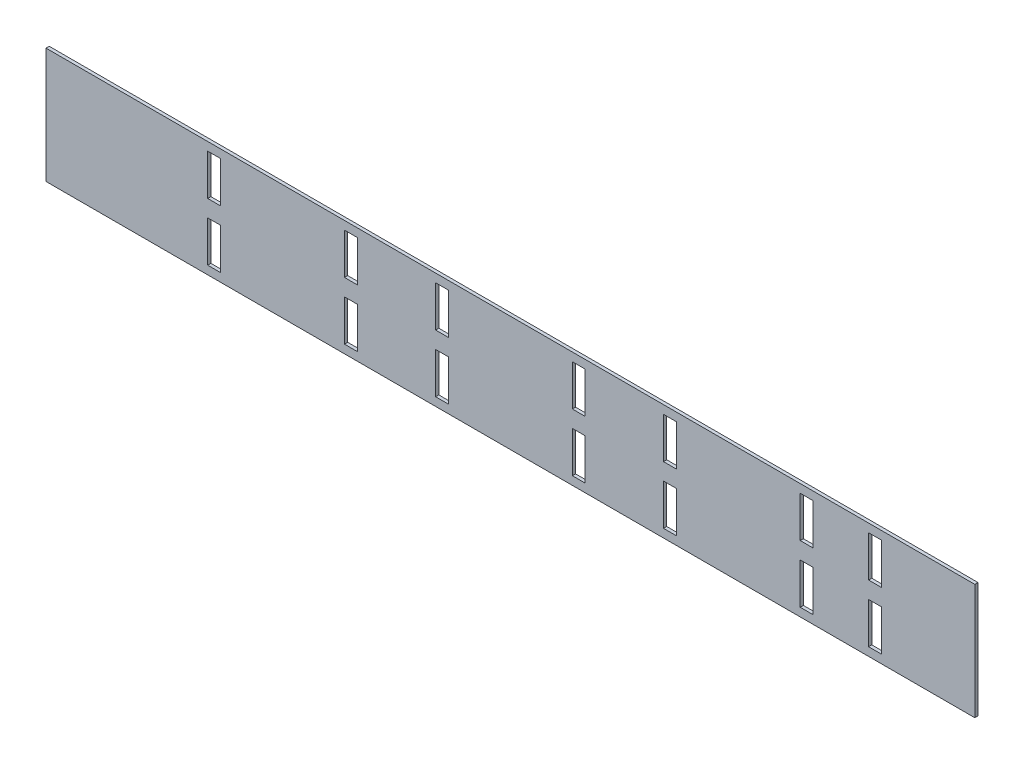
SolidWorks part; units mm, degrees
material "Acrylic (Medium-high impact)"
ref_plane "Front Plane" through (0, 0, 0) normal (0, 0, 1) x (1, 0, 0)
ref_plane "Top Plane" through (0, 0, 0) normal (0, 1, 0) x (1, 0, 0)
ref_plane "Right Plane" through (0, 0, 0) normal (1, 0, 0) x (0, 0, -1)
sketch "Sketch12" plane through (0, 0, 0) normal (0, 0, 1) x (1, 0, 0)
  line L0 (-148.2488, 58.6659) -> (312.4252, 58.6659)
  line L1 (-148.2488, 58.6659) -> (-148.2488, 1.3659)
  line L2 (-148.2488, 1.3659) -> (312.4252, 1.3659)
  line L3 (312.4252, 58.6659) -> (312.4252, 1.3659)
  line L4 (158.0086, 54.5003) -> (164.4098, 54.5003)
  line L5 (158.0086, 54.5003) -> (158.0086, 34.1803)
  line L6 (158.0086, 34.1803) -> (164.4098, 34.1803)
  line L7 (164.4098, 54.5003) -> (164.4098, 34.1803)
  line L8 (112.7966, 54.5003) -> (119.1978, 54.5003)
  line L9 (112.7966, 54.5003) -> (112.7966, 34.1803)
  line L10 (112.7966, 34.1803) -> (119.1978, 34.1803)
  line L11 (119.1978, 54.5003) -> (119.1978, 34.1803)
  line L12 (112.7966, 25.8491) -> (119.1978, 25.8491)
  line L13 (112.7966, 25.8491) -> (112.7966, 5.5291)
  line L14 (112.7966, 5.5291) -> (119.1978, 5.5291)
  line L15 (119.1978, 25.8491) -> (119.1978, 5.5291)
  line L16 (158.0086, 25.8491) -> (164.4098, 25.8491)
  line L17 (158.0086, 25.8491) -> (158.0086, 5.5291)
  line L18 (158.0086, 5.5291) -> (164.4098, 5.5291)
  line L19 (164.4098, 25.8491) -> (164.4098, 5.5291)
  line L20 (225.8266, 54.5003) -> (232.2278, 54.5003)
  line L21 (225.8266, 54.5003) -> (225.8266, 34.1803)
  line L22 (225.8266, 34.1803) -> (232.2278, 34.1803)
  line L23 (232.2278, 54.5003) -> (232.2278, 34.1803)
  line L24 (225.8266, 25.8491) -> (232.2278, 25.8491)
  line L25 (225.8266, 25.8491) -> (225.8266, 5.5291)
  line L26 (225.8266, 5.5291) -> (232.2278, 5.5291)
  line L27 (232.2278, 25.8491) -> (232.2278, 5.5291)
  line L28 (259.7356, 54.5003) -> (266.1368, 54.5003)
  line L29 (259.7356, 54.5003) -> (259.7356, 34.1803)
  line L30 (259.7356, 34.1803) -> (266.1368, 34.1803)
  line L31 (266.1368, 54.5003) -> (266.1368, 34.1803)
  line L32 (259.7356, 25.8491) -> (266.1368, 25.8491)
  line L33 (259.7356, 25.8491) -> (259.7356, 5.5291)
  line L34 (259.7356, 5.5291) -> (266.1368, 5.5291)
  line L35 (266.1368, 25.8491) -> (266.1368, 5.5291)
  line L36 (44.9786, 54.5003) -> (51.3798, 54.5003)
  line L37 (44.9786, 54.5003) -> (44.9786, 34.1803)
  line L38 (44.9786, 34.1803) -> (51.3798, 34.1803)
  line L39 (51.3798, 54.5003) -> (51.3798, 34.1803)
  line L40 (44.9786, 25.8491) -> (51.3798, 25.8491)
  line L41 (44.9786, 25.8491) -> (44.9786, 5.5291)
  line L42 (44.9786, 5.5291) -> (51.3798, 5.5291)
  line L43 (51.3798, 25.8491) -> (51.3798, 5.5291)
  line L44 (-0.2334, 54.5003) -> (6.1678, 54.5003)
  line L45 (-0.2334, 54.5003) -> (-0.2334, 34.1803)
  line L46 (-0.2334, 34.1803) -> (6.1678, 34.1803)
  line L47 (6.1678, 54.5003) -> (6.1678, 34.1803)
  line L48 (-0.2334, 25.8491) -> (6.1678, 25.8491)
  line L49 (-0.2334, 25.8491) -> (-0.2334, 5.5291)
  line L50 (-0.2334, 5.5291) -> (6.1678, 5.5291)
  line L51 (6.1678, 25.8491) -> (6.1678, 5.5291)
  line L52 (-68.0514, 54.5003) -> (-61.6502, 54.5003)
  line L53 (-68.0514, 54.5003) -> (-68.0514, 34.1803)
  line L54 (-68.0514, 34.1803) -> (-61.6502, 34.1803)
  line L55 (-61.6502, 54.5003) -> (-61.6502, 34.1803)
  line L56 (-68.0514, 25.8491) -> (-61.6502, 25.8491)
  line L57 (-68.0514, 25.8491) -> (-68.0514, 5.5291)
  line L58 (-68.0514, 5.5291) -> (-61.6502, 5.5291)
  line L59 (-61.6502, 25.8491) -> (-61.6502, 5.5291)
extrude "Boss-Extrude5" add sketch "Sketch12" along normal blind 1.5875
